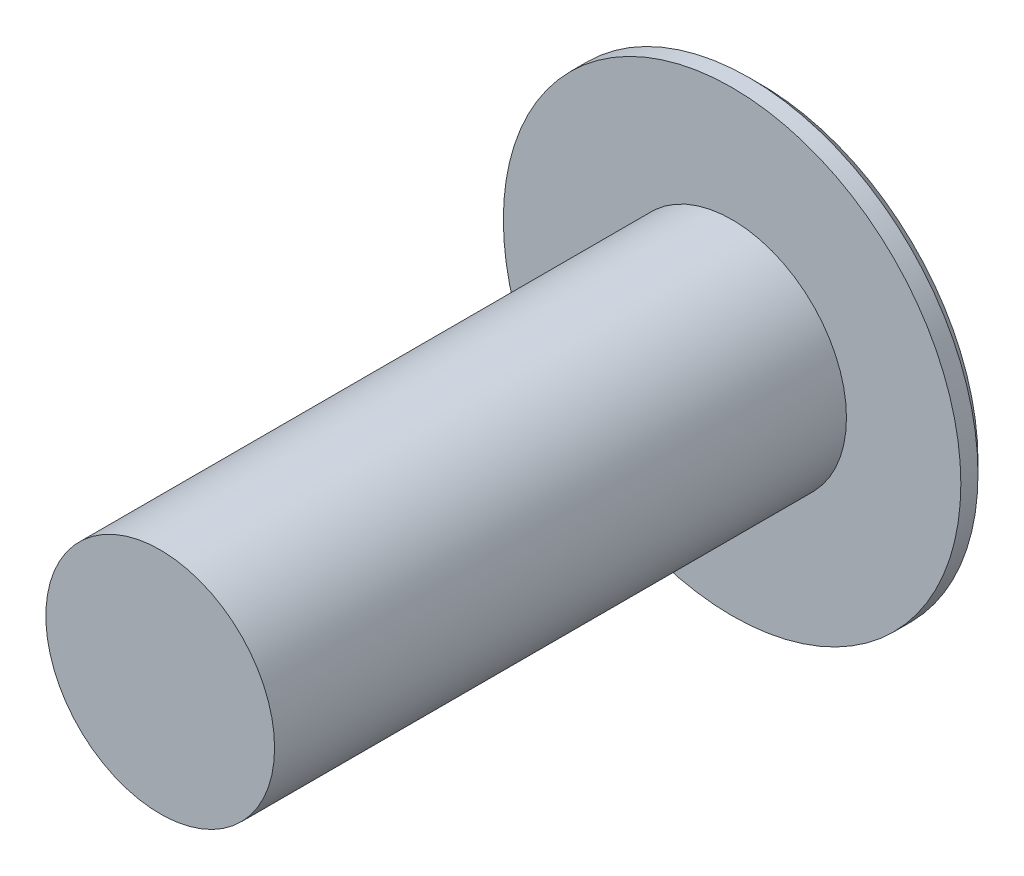
SolidWorks part; units mm, degrees
ref_plane "Front Plane" through (0, 0, 0) normal (0, 0, 1) x (1, 0, 0)
ref_plane "Top Plane" through (0, 0, 0) normal (0, 1, 0) x (1, 0, 0)
ref_plane "Right Plane" through (0, 0, 0) normal (1, 0, 0) x (0, 0, -1)
sketch "Sketch2" plane through (0, 0, 0) normal (0, 0, 1) x (1, 0, 0)
  circle A0 centre (0, 0) radius 20
  dimension "D1" = 40
extrude "Boss-Extrude1" add sketch "Sketch2" along normal blind 100
sketch "Sketch3" plane through (0, 0, 0) normal (0, 0, -1) x (-1, 0, 0)
  circle A0 centre (0, 0) radius 40
extrude "Boss-Extrude2" add sketch "Sketch3" along normal blind 5
chamfer "Chamfer1" distance 2 angle 45 1 edges at (-40, 0, -5)
equation "\"deg\"=2"
